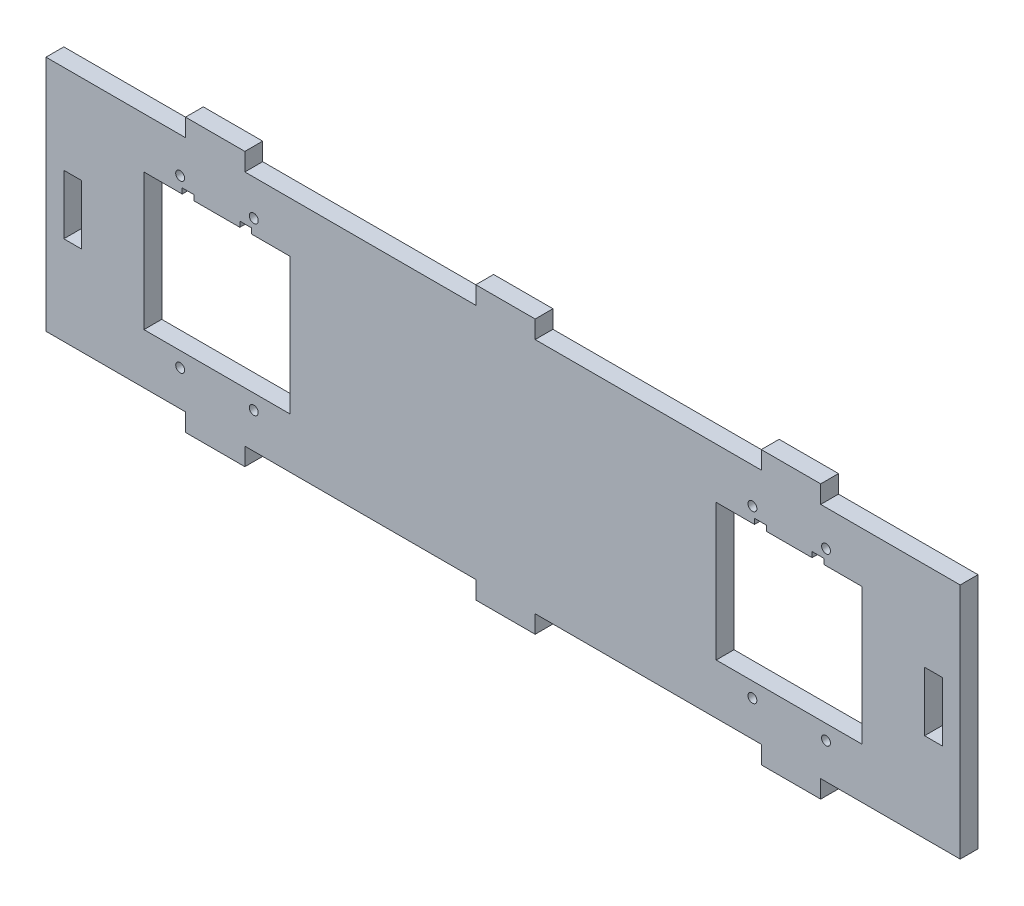
SolidWorks part; units mm, degrees
ref_plane "前视基准面" through (0, 0, 0) normal (0, 0, 1) x (1, 0, 0)
ref_plane "上视基准面" through (0, 0, 0) normal (0, 1, 0) x (1, 0, 0)
ref_plane "右视基准面" through (0, 0, 0) normal (1, 0, 0) x (0, 0, -1)
sketch "草图1" plane through (0, 0, 0) normal (0, 0, 1) x (1, 0, 0)
  line L0 (-43.5, -20) -> (-4.5995, -20)
  line L1 (-77, -20) -> (-53.5, -20)
  line L2 (-77, -20) -> (-77, 20)
  line L3 (-77, 20) -> (-53.5, 20)
  line L4 (77, -20) -> (77, 20)
  line L5 (-77, -20) -> (77, 20) construction
  line L6 (-77, 20) -> (-44.35, 11.5195) construction
  line L7 (-74, 5) -> (-71, 5)
  line L8 (-74, 5) -> (-74, -5)
  line L9 (-74, -5) -> (-71, -5)
  line L10 (-71, 5) -> (-71, -5)
  line L11 (-74, 5) -> (-71, -5) construction
  line L12 (-74, -5) -> (-71, 5) construction
  line L14 (-53.5, -20) -> (-53.5, -23)
  line L15 (-53.5, -23) -> (-43.5, -23)
  line L16 (-43.5, -20) -> (-43.5, -23)
  line L17 (5.4005, -20) -> (43.5, -20)
  line L19 (-4.5995, -20) -> (-4.5995, -23)
  line L20 (-4.5995, -23) -> (5.4005, -23)
  line L21 (5.4005, -20) -> (5.4005, -23)
  line L22 (0, 0) -> (23.187, 0) construction
  line L23 (23.187, 0) -> (0, 0) construction
  line L24 (0, 0) -> (0, 13.7159) construction
  line L25 (74, -5) -> (71, -5)
  line L26 (71, 5) -> (71, -5)
  line L27 (74, 5) -> (71, 5)
  line L28 (74, 5) -> (74, -5)
  line L29 (43.5, -20) -> (43.5, -23)
  line L30 (53.5, -23) -> (43.5, -23)
  line L31 (53.5, -20) -> (53.5, -23)
  line L32 (53.5, -20) -> (77, -20)
  line L33 (53.5, 23) -> (43.5, 23)
  line L34 (53.5, 20) -> (53.5, 23)
  line L35 (43.5, 20) -> (43.5, 23)
  line L36 (5.4005, 20) -> (5.4005, 23)
  line L37 (-4.5995, 23) -> (5.4005, 23)
  line L38 (-4.5995, 20) -> (-4.5995, 23)
  line L39 (-43.5, 20) -> (-43.5, 23)
  line L40 (-53.5, 23) -> (-43.5, 23)
  line L41 (-53.5, 20) -> (-53.5, 23)
  line L42 (-43.5, 20) -> (-4.5995, 20)
  line L43 (5.4005, 20) -> (43.5, 20)
  line L44 (53.5, 20) -> (77, 20)
  line L45 (-48.2, 0) -> (-49.5187, 0) construction
  line L46 (-60.5, 11.5) -> (-54.05, 11.5)
  line L47 (-60.5, 11.5) -> (-60.5, -11.5)
  line L48 (-60.5, -11.5) -> (-35.9, -11.5)
  line L49 (-35.9, 11.5) -> (-35.9, -11.5)
  line L50 (-60.5, 11.5) -> (-35.9, -11.5) construction
  line L51 (-60.5, -11.5) -> (-35.9, 11.5) construction
  line L52 (-48.2, 0) -> (-48.2, -9.2982) construction
  line L53 (-52.05, 11.5) -> (-44.35, 11.5)
  line L55 (-52.05, 11.5) -> (-52.05, 12.4016)
  line L56 (-52.05, 12.4016) -> (-54.05, 12.4016)
  line L57 (-54.05, 11.5) -> (-54.05, 12.4016)
  line L58 (-42.35, 11.5) -> (-42.35, 12.4016)
  line L59 (-44.35, 12.4016) -> (-42.35, 12.4016)
  line L60 (-44.35, 11.5) -> (-44.35, 12.4016)
  line L61 (-42.35, 11.5) -> (-35.9, 11.5)
  line L62 (-37.7208, 9.7976) -> (77, -20) construction
  line L63 (52.05, 11.5) -> (52.05, 12.4016)
  line L64 (52.05, 12.4016) -> (54.05, 12.4016)
  line L65 (54.05, 11.5) -> (54.05, 12.4016)
  line L66 (60.5, 11.5) -> (54.05, 11.5)
  line L67 (60.5, 11.5) -> (60.5, -11.5)
  line L68 (60.5, -11.5) -> (35.9, -11.5)
  line L69 (35.9, 11.5) -> (35.9, -11.5)
  line L70 (42.35, 11.5) -> (35.9, 11.5)
  line L71 (42.35, 11.5) -> (42.35, 12.4016)
  line L72 (44.35, 12.4016) -> (42.35, 12.4016)
  line L73 (44.35, 11.5) -> (44.35, 12.4016)
  line L74 (52.05, 11.5) -> (44.35, 11.5)
  circle A0 centre (-54.4, -14) radius 0.75
  circle A1 centre (-54.4, 14) radius 0.75
  circle A2 centre (-42, -14) radius 0.75
  circle A3 centre (-42, 14) radius 0.75
  circle A4 centre (42, -14) radius 0.75
  circle A5 centre (54.4, -14) radius 0.75
  circle A6 centre (54.4, 14) radius 0.75
  circle A7 centre (42, 14) radius 0.75
  point P0 (0, 0)
  point P6 (-72.5, 0)
  point P14 (0, -20)
  point P16 (-53.5, -21.5)
  point P44 (-48.2, 0)
  dimension "D11" = 1.5
  dimension "D1" = 154
  dimension "D2" = 40
  dimension "D3" = 10
  dimension "D4" = 3
  dimension "D5" = 3
  dimension "D6" = 23.5
  dimension "D7" = 24.6
  dimension "D8" = 23
  dimension "D9" = 2.5
  dimension "D10" = 6.1
  dimension "D12" = 16.5
extrude "凸台-拉伸1" add sketch "草图1" along normal blind 3
